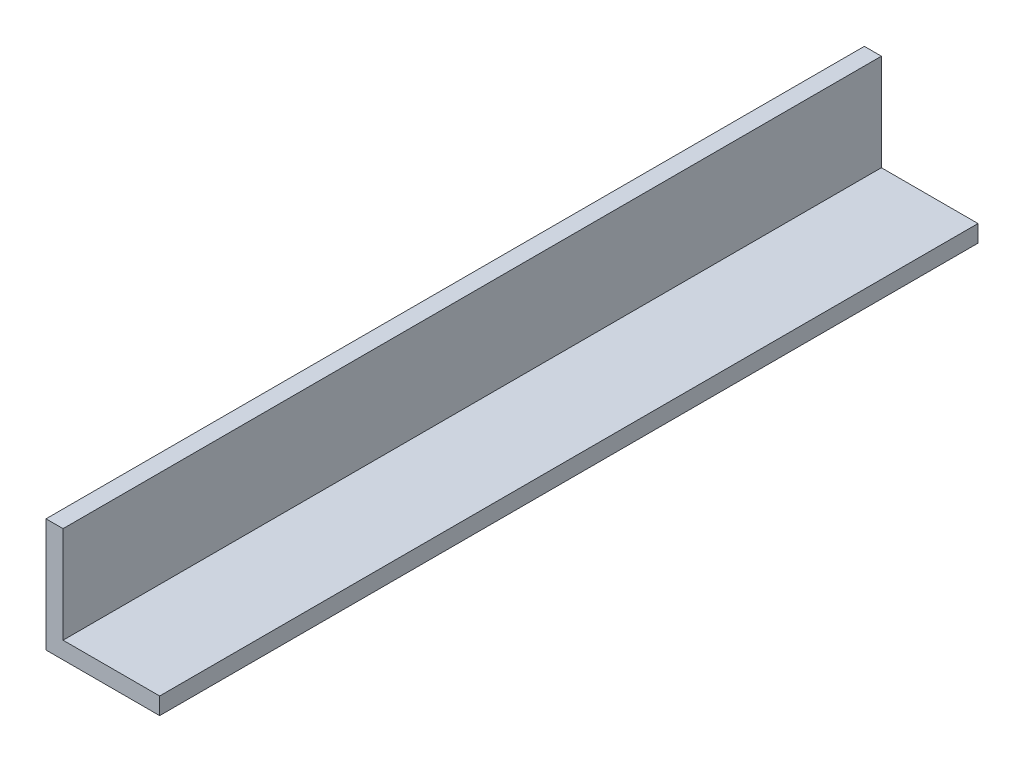
SolidWorks part; units mm, degrees
ref_plane "Front Plane" through (0, 0, 0) normal (0, 0, 1) x (1, 0, 0)
ref_plane "Top Plane" through (0, 0, 0) normal (0, 1, 0) x (1, 0, 0)
ref_plane "Right Plane" through (0, 0, 0) normal (1, 0, 0) x (0, 0, -1)
sketch "Sketch1" plane through (0, 0, 0) normal (0, 0, 1) x (1, 0, 0)
  line L0 (0, 0) -> (20, 0)
  line L1 (20, 0) -> (20, 3)
  line L2 (20, 3) -> (3, 3)
  line L3 (0, 0) -> (0, 20)
  line L4 (0, 20) -> (3, 20)
  line L5 (3, 20) -> (3, 3)
  dimension "D1" = 3
  dimension "D2" = 3
  dimension "D3" = 20
  dimension "D4" = 20
extrude "Boss-Extrude1" add sketch "Sketch1" along normal blind 144
